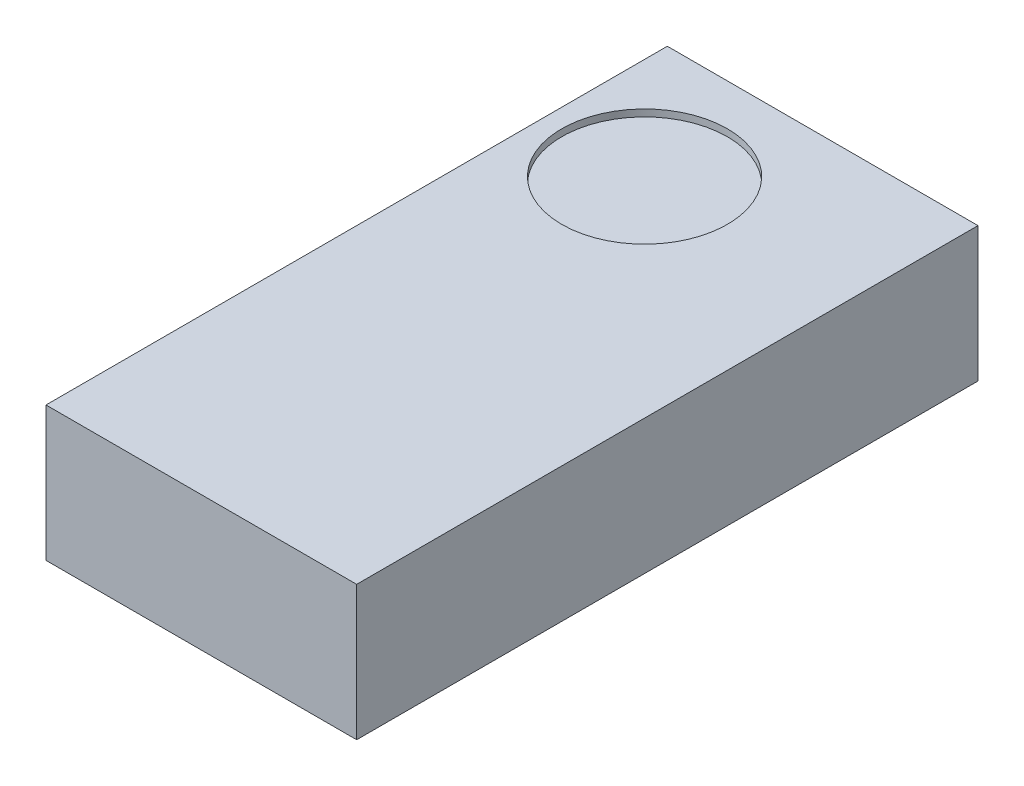
SolidWorks part; units mm, degrees
material "Chrome Stainless Steel"
ref_plane "Front Plane" through (0, 0, 0) normal (0, 0, 1) x (1, 0, 0)
ref_plane "Top Plane" through (0, 0, 0) normal (0, 1, 0) x (1, 0, 0)
ref_plane "Right Plane" through (0, 0, 0) normal (1, 0, 0) x (0, 0, -1)
sketch "Sketch1" plane through (0, 0, 0) normal (0, 1, 0) x (1, 0, 0)
  line L1 (-57.15, 114.3) -> (57.15, 114.3)
  line L2 (-57.15, 114.3) -> (-57.15, -114.3)
  line L3 (-57.15, -114.3) -> (57.15, -114.3)
  line L4 (57.15, 114.3) -> (57.15, -114.3)
  line L5 (-57.15, 114.3) -> (57.15, -114.3) construction
  line L6 (-57.15, -114.3) -> (57.15, 114.3) construction
  point P0 (0, 0)
extrude "Boss-Extrude1" add sketch "Sketch1" along normal blind 49.53
sketch "Sketch2" plane through (0, 49.53, 0) normal (0, 1, 0) x (1, 0, 0)
  line L0 (-57.15, 114.3) -> (-57.15, -114.3) construction
  line L1 (57.15, 114.3) -> (-57.15, 114.3) construction
  circle A0 centre (-19.812, 68.58) radius 30.48
  dimension "D1" = 37.338
  dimension "D2" = 45.72
extrude "Cut-Extrude1" cut sketch "Sketch2" against normal blind 2.54
